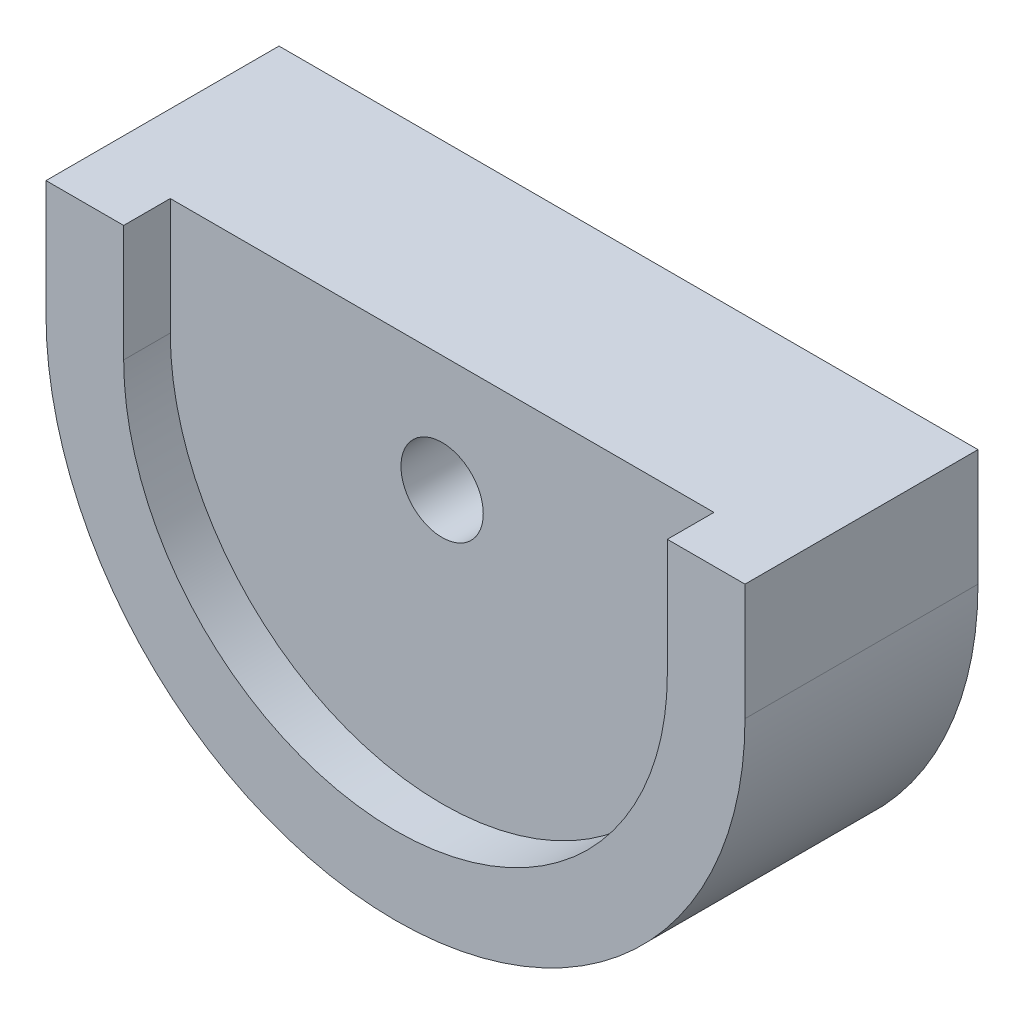
SolidWorks part; units mm, degrees
ref_plane "前视基准面" through (0, 0, 0) normal (0, 0, 1) x (1, 0, 0)
ref_plane "上视基准面" through (0, 0, 0) normal (0, 1, 0) x (1, 0, 0)
ref_plane "右视基准面" through (0, 0, 0) normal (1, 0, 0) x (0, 0, -1)
other "Configuration Table"
sketch "草图1" plane through (0, 0, 0) normal (0, 0, 1) x (1, 0, 0)
  line L2 (-22.5, 0) -> (-22.5, 22.5)
  line L3 (-22.5, 22.5) -> (22.5, 22.5)
  line L4 (22.5, 0) -> (22.5, 22.5)
  arc A0 (-22.5, 0) -> (22.5, 0) centre (0, 0) ccw
  dimension "D1" = 45
  dimension "D2" = 22.5
  dimension "D3" = 45
extrude "凸台-拉伸1" add sketch "草图1" along normal blind 25
sketch "草图2" plane through (0, 0, 25) normal (0, 0, 1) x (1, 0, 0)
  line L0 (22.5, 22.5) -> (-22.5, 22.5) construction
  line L1 (-17.5, 22.5) -> (17.5, 22.5)
  line L2 (-17.5, 22.5) -> (-17.5, 0)
  line L3 (-17.5, 0) -> (17.5, 0)
  line L4 (17.5, 22.5) -> (17.5, 0)
  circle A0 centre (0, 0) radius 17.5
  line M4 (22.5, 22.5) -> (-22.5, 22.5)
  dimension "D1" = 35
extrude "切除-拉伸1" cut sketch "草图2" against normal blind 3 contours A0 L4 L2 M4 | L3 A0 | L3 A0
sketch "草图3" plane through (0, 0, 22) normal (0, 0, 1) x (1, 0, 0)
  line L0 (22.5, 0) -> (22.5, 22.5) construction
  line L1 (-22.5, 22.5) -> (22.5, 22.5)
  line L2 (-22.5, 22.5) -> (-22.5, 7.5)
  line L3 (-22.5, 7.5) -> (22.5, 7.5)
  line L4 (22.5, 22.5) -> (22.5, 7.5)
  dimension "D1" = 15
extrude "切除-拉伸2" cut sketch "草图3" against normal blind 35 and the other way blind 20
sketch "草图4" plane through (0, 0, 22) normal (0, 0, 1) x (1, 0, 0)
  circle A0 centre (0, 0) radius 2.65
  dimension "D1" = 5.3
extrude "切除-拉伸3" cut sketch "草图4" against normal blind 35
sketch "草图5" plane through (0, 0, 0) normal (0, 0, -1) x (-1, 0, 0)
  circle A0 centre (0, 0) radius 4.75
  dimension "D1" = 9.5
extrude "切除-拉伸4" cut sketch "草图5" against normal blind 15
sketch "草图6" plane through (0, 0, 0) normal (0, 0, -1) x (-1, 0, 0)
  circle A0 centre (0, 0) radius 24.8918
extrude "切除-拉伸5" cut sketch "草图6" against normal blind 10
